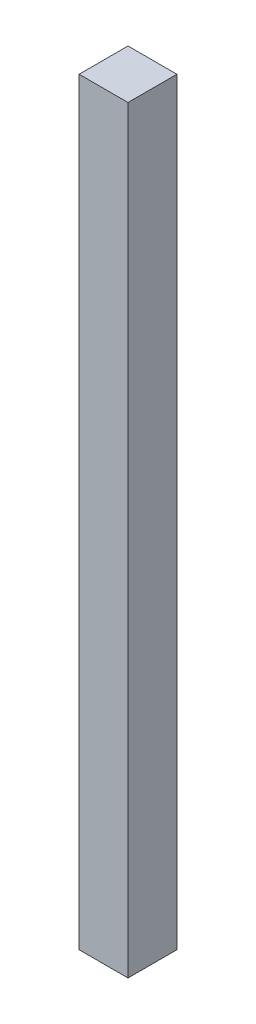
SolidWorks part; units mm, degrees
ref_plane "Front Plane" through (0, 0, 0) normal (0, 0, 1) x (1, 0, 0)
ref_plane "Top Plane" through (0, 0, 0) normal (0, 1, 0) x (1, 0, 0)
ref_plane "Right Plane" through (0, 0, 0) normal (1, 0, 0) x (0, 0, -1)
sketch "Sketch1" plane through (0, 0, 0) normal (0, 1, 0) x (1, 0, 0)
  line L1 (0, 0) -> (20, 0)
  line L2 (0, 0) -> (0, 20)
  line L3 (0, 20) -> (20, 20)
  line L4 (20, 0) -> (20, 20)
  dimension "D1" = 20
  dimension "D2" = 20
extrude "Boss-Extrude1" add sketch "Sketch1" along normal blind 310 contours L3 L4 L1 L2
